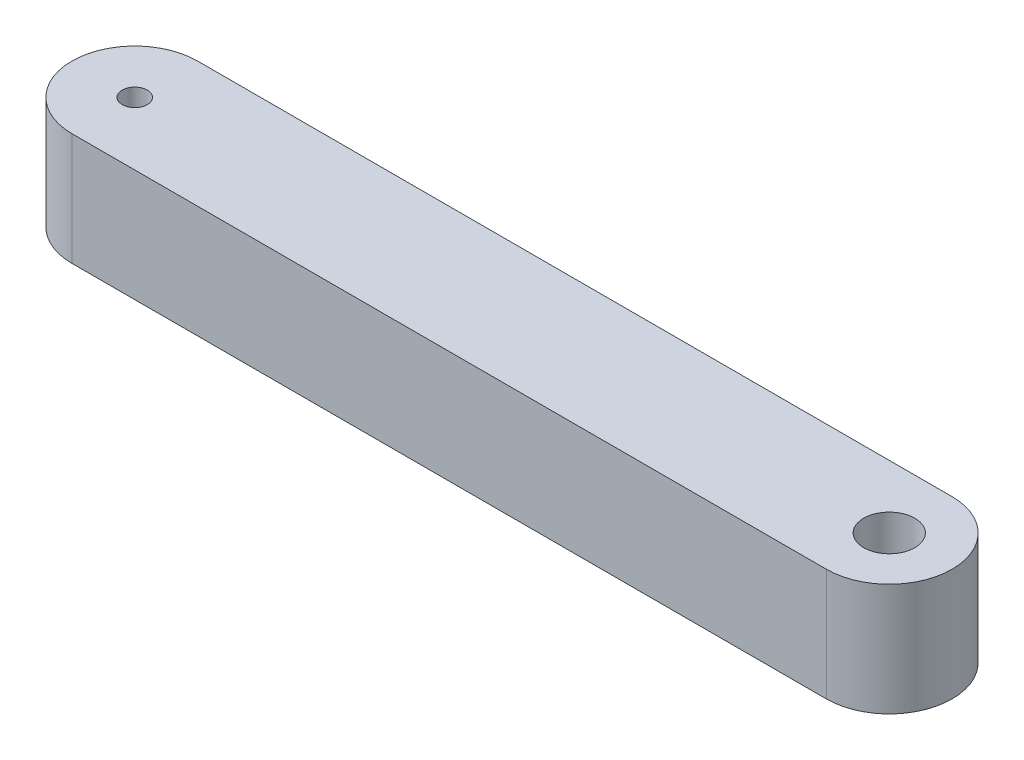
SolidWorks part; units mm, degrees
material "3.0205 (EN-AW 1200)"
ref_plane "Front Plane" through (0, 0, 0) normal (0, 0, 1) x (1, 0, 0)
ref_plane "Top Plane" through (0, 0, 0) normal (0, 1, 0) x (1, 0, 0)
ref_plane "Right Plane" through (0, 0, 0) normal (1, 0, 0) x (0, 0, -1)
sketch "Sketch1" plane through (0, 0, 0) normal (0, 1, 0) x (1, 0, 0)
  line L1 (-90, -15) -> (90, -15)
  line L3 (-90, 15) -> (90, 15)
  line L5 (0, 15) -> (0, -15) construction
  line L6 (-93, 0) -> (90, 0) construction
  circle A0 centre (-90, 0) radius 3
  circle A1 centre (90, 0) radius 3
  arc A4 (-90, -15) -> (-90, 15) centre (-90, 0) cw
  arc A5 (90, -15) -> (90, 15) centre (90, 0) ccw
  point P0 (0, 0)
  dimension "D1" = 6
  dimension "D7" = 6
  dimension "D2" = 90
  dimension "D3" = 180
  dimension "D4" = 30
  dimension "D6" = 0
extrude "Boss-Extrude2" add sketch "Sketch1" along normal blind 26.8
sketch "Sketch2" plane through (0, 0, 0) normal (0, -1, 0) x (1, 0, 0)
  circle A0 centre (90, 0) radius 6.1
  dimension "D1" = 12.2
extrude "Cut-Extrude1" cut sketch "Sketch2" against normal blind 26.8
sketch "Sketch3" plane through (0, 0, 0) normal (0, -1, 0) x (1, 0, 0)
  circle A0 centre (90, 0) radius 6.5
  dimension "D1" = 13
extrude "Cut-Extrude2" cut sketch "Sketch3" against normal blind 5
equation "\"link_thickness\" = 50"
